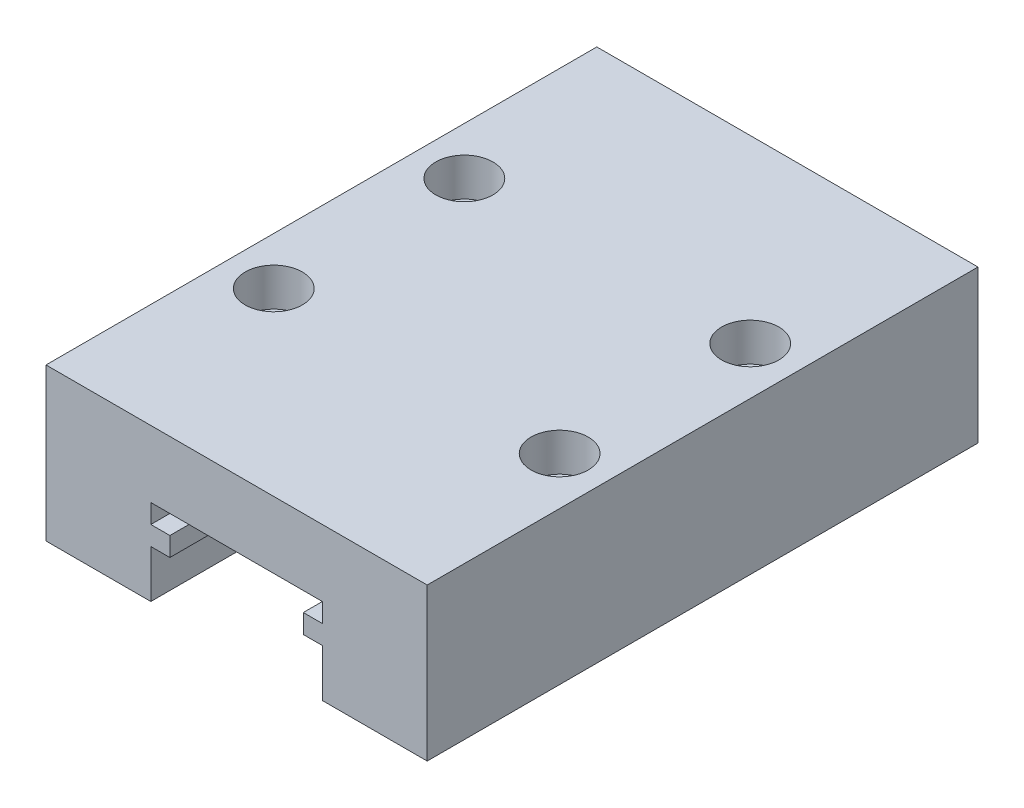
SolidWorks part; units mm, degrees
ref_plane "前视基准面" through (0, 0, 0) normal (0, 0, 1) x (1, 0, 0)
ref_plane "上视基准面" through (0, 0, 0) normal (0, 1, 0) x (1, 0, 0)
ref_plane "右视基准面" through (0, 0, 0) normal (1, 0, 0) x (0, 0, -1)
sketch "草图1" plane through (0, 0, 0) normal (0, 0, 1) x (1, 0, 0)
  line L0 (0, 0) -> (0, 12.6766) construction
  line L1 (10, 8) -> (-10, 8)
  line L2 (-10, 8) -> (-10, 0)
  line L3 (-10, 0) -> (-4.5, 0)
  line L7 (-4.5, 4.5) -> (4.5, 4.5)
  line L8 (4.5, 3.5) -> (4.5, 4.5)
  line L11 (10, 0) -> (4.5, 0)
  line L12 (10, 8) -> (10, 0)
  line L13 (-4.5, 4.5) -> (-4.5, 3.5)
  line L14 (-4.5, 3.5) -> (-3.5, 3.5)
  line L15 (-3.5, 3.5) -> (-3.5, 2.5)
  line L16 (-3.5, 2.5) -> (-4.5, 2.5)
  line L17 (-4.5, 2.5) -> (-4.5, 0)
  line L18 (4.5, 3.5) -> (3.5, 3.5)
  line L19 (3.5, 3.5) -> (3.5, 2.5)
  line L20 (3.5, 2.5) -> (4.5, 2.5)
  line L21 (4.5, 2.5) -> (4.5, 0)
  point P3 (0, 0)
  point P12 (0, 4.5)
  point P17 (0, 8)
  dimension "D1" = 20
  dimension "D2" = 8
  dimension "D3" = 9
  dimension "D4" = 5.5
  dimension "D5" = 1
  dimension "D6" = 1
  dimension "D7" = 1
  dimension "D8" = 4.5
extrude "凸台-拉伸1" add sketch "草图1" along normal blind 28.9
sketch "草图2" plane through (0, 8, 0) normal (0, 1, 0) x (1, 0, 0)
  line L0 (0, 0) -> (0, -28.9) construction
  line L1 (10, 0) -> (-10, 0) construction
  line L2 (10, -28.9) -> (-10, -28.9) construction
  line L3 (-10, -14.45) -> (10, -14.45) construction
  line L4 (-10, -28.9) -> (-10, 0) construction
  line L5 (10, -28.9) -> (10, 0) construction
  circle A0 centre (-7.5, -9.45) radius 1.5
  circle A1 centre (-7.5, -19.45) radius 1.5
  circle A2 centre (7.5, -19.45) radius 1.5
  circle A3 centre (7.5, -9.45) radius 1.5
  dimension "D1" = 3
  dimension "D2" = 10
  dimension "D3" = 7.5
extrude "切除-拉伸1" cut sketch "草图2" against normal blind 2
